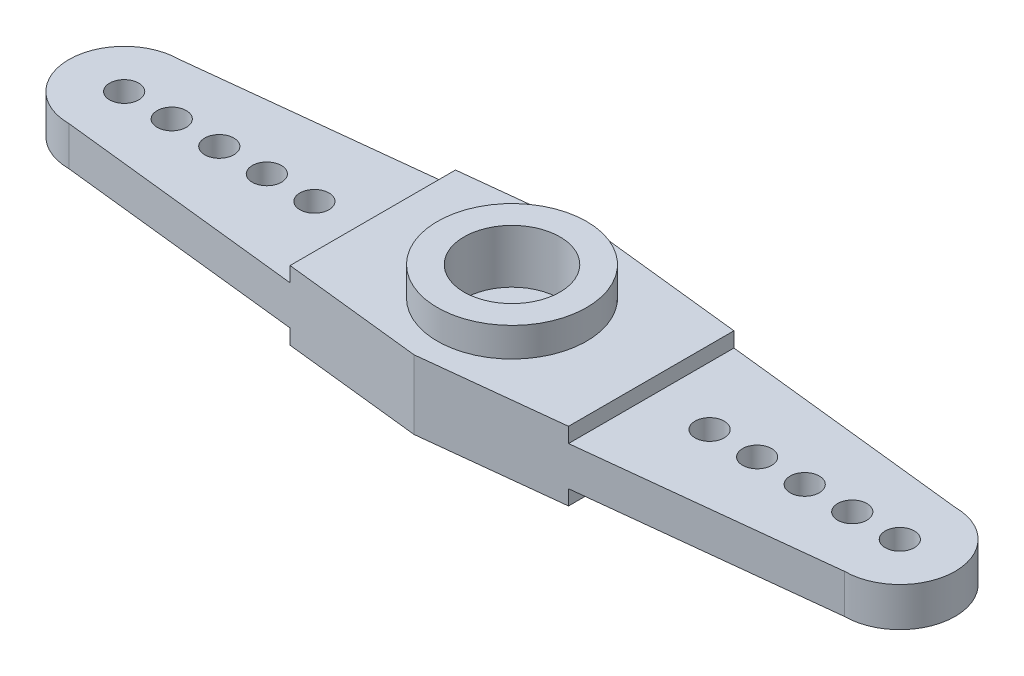
SolidWorks part; units mm, degrees
ref_plane "Front Plane" through (0, 0, 0) normal (0, 0, 1) x (1, 0, 0)
ref_plane "Top Plane" through (0, 0, 0) normal (0, 1, 0) x (1, 0, 0)
ref_plane "Right Plane" through (0, 0, 0) normal (1, 0, 0) x (0, 0, -1)
sketch "Sketch1" plane through (0, 0, 0) normal (0, 1, 0) x (1, 0, 0)
  line L3 (0, 0) -> (0, 12.78) construction
  line L4 (0, 6.39) -> (28.89, 6.39) construction
  line L5 (0, 12.78) -> (25.28, 10)
  line L6 (0, 0) -> (25.28, 2.78)
  line L7 (25.28, 10) -> (25.28, 2.78) construction
  line L8 (0, 0) -> (-25.28, 2.78)
  line L9 (0, 12.78) -> (-25.28, 10)
  arc A4 (25.28, 2.78) -> (25.28, 10) centre (25.28, 6.39) ccw
  circle A5 centre (25.28, 6.39) radius 0.95
  circle A11 centre (22.18, 6.39) radius 0.95
  circle A12 centre (19.08, 6.39) radius 0.95
  circle A13 centre (15.98, 6.39) radius 0.95
  circle A14 centre (12.88, 6.39) radius 0.95
  circle A15 centre (-12.88, 6.39) radius 0.95
  circle A16 centre (-15.98, 6.39) radius 0.95
  circle A17 centre (-19.08, 6.39) radius 0.95
  circle A18 centre (-22.18, 6.39) radius 0.95
  circle A19 centre (-25.28, 6.39) radius 0.95
  arc A20 (-25.28, 2.78) -> (-25.28, 10) centre (-25.28, 6.39) cw
  dimension "D1" = 12.78
  dimension "D5" = 5
  dimension "D6" = 3.1
  dimension "D3" = 3.61
  dimension "D4" = 1.9
  dimension "D2" = 28.89
extrude "Boss-Extrude1" add sketch "Sketch1" along normal blind 2.55
sketch "Sketch2" plane through (0, 2.55, 0) normal (0, 1, 0) x (1, 0, 0)
  line L0 (-9.075, 11.782) -> (-9.075, 0.998)
  line L1 (9.075, 11.782) -> (9.075, 0.998)
  line L2 (-25.28, 2.78) -> (0, 0) construction
  line L3 (0, 12.78) -> (-25.28, 10) construction
  line L4 (25.28, 10) -> (0, 12.78) construction
  line L5 (0, 0) -> (25.28, 2.78) construction
  line L6 (-9.075, 11.782) -> (0, 12.78)
  line L7 (0, 12.78) -> (9.075, 11.782)
  line L8 (-9.075, 0.998) -> (0, 0)
  line L9 (0, 0) -> (9.075, 0.998)
  dimension "D1" = 18.15
extrude "Boss-Extrude2" add sketch "Sketch2" along normal blind 0.975 and the other way blind 3.525
sketch "Sketch3" plane through (0, -0.975, 0) normal (0, -1, 0) x (1, 0, 0)
  line L0 (0, 0) -> (0, -12.78) construction
  line L1 (-9.075, -6.39) -> (9.075, -6.39) construction
  line L2 (-9.075, -11.782) -> (-9.075, -0.998) construction
  line L3 (9.075, -0.998) -> (9.075, -11.782) construction
  circle A0 centre (0, -6.39) radius 4.135
  dimension "D1" = 8.27
extrude "Cut-Extrude1" cut sketch "Sketch3" against normal blind 1.95
sketch "Sketch4" plane through (0, 3.525, 0) normal (0, 1, 0) x (1, 0, 0)
  line L0 (-9.075, 6.39) -> (9.075, 6.39) construction
  line L1 (0, 12.78) -> (0, 0) construction
  line L2 (-9.075, 11.782) -> (-9.075, 0.998) construction
  line L3 (9.075, 0.998) -> (9.075, 11.782) construction
  circle A0 centre (0, 6.39) radius 4.865
  dimension "D1" = 9.73
extrude "Boss-Extrude3" add sketch "Sketch4" along normal blind 1.9
sketch "Sketch5" plane through (0, 5.425, 0) normal (0, 1, 0) x (1, 0, 0)
  circle A0 centre (0, 6.39) radius 3.125
  circle A1 centre (0, 6.39) radius 4.865 construction
  dimension "D1" = 6.25
extrude "Cut-Extrude2" cut sketch "Sketch5" against normal blind 3.49
